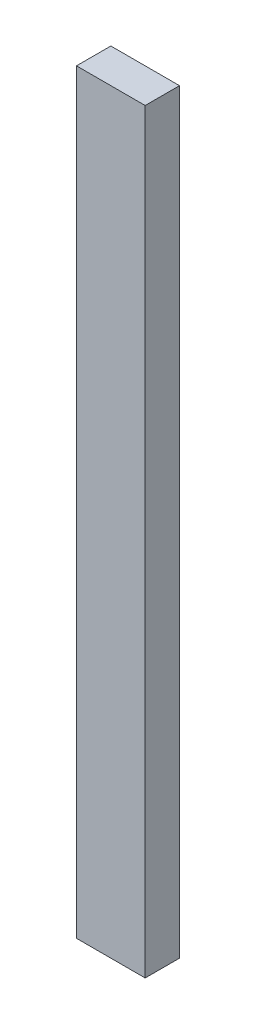
SolidWorks part; units mm, degrees
ref_plane "Front Plane" through (0, 0, 0) normal (0, 0, 1) x (1, 0, 0)
ref_plane "Top Plane" through (0, 0, 0) normal (0, 1, 0) x (1, 0, 0)
ref_plane "Right Plane" through (0, 0, 0) normal (1, 0, 0) x (0, 0, -1)
sketch "Sketch1" plane through (0, 0, 0) normal (0, 0, 1) x (1, 0, 0)
  line L5 (-12.7, -139.7) -> (12.7, -139.7)
  line L6 (-12.7, -139.7) -> (-12.7, 139.7)
  line L7 (-12.7, 139.7) -> (12.7, 139.7)
  line L8 (12.7, -139.7) -> (12.7, 139.7)
  line L9 (-12.7, -139.7) -> (12.7, 139.7) construction
  line L10 (-12.7, 139.7) -> (12.7, -139.7) construction
  point P0 (0, 0)
  dimension "D1" = 25.4
  dimension "D2" = 279.4
extrude "Boss-Extrude1" add sketch "Sketch1" against normal blind 12.7
